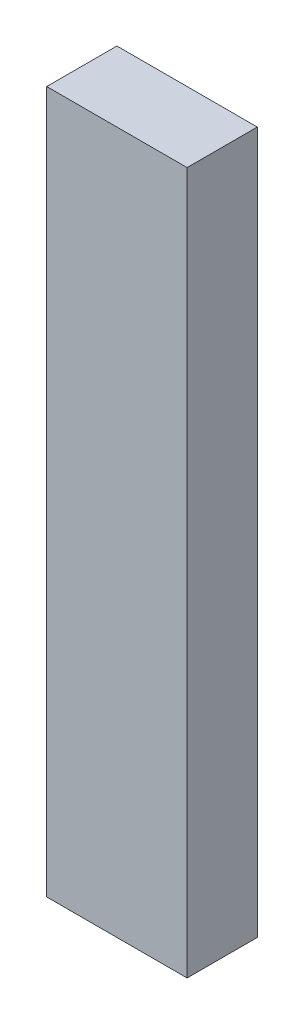
SolidWorks part; units mm, degrees
ref_plane "Front Plane" through (0, 0, 0) normal (0, 0, 1) x (1, 0, 0)
ref_plane "Top Plane" through (0, 0, 0) normal (0, 1, 0) x (1, 0, 0)
ref_plane "Right Plane" through (0, 0, 0) normal (1, 0, 0) x (0, 0, -1)
sketch "Sketch1" plane through (0, 0, 0) normal (0, 1, 0) x (1, 0, 0)
  line L1 (25, -25) -> (-25, -25)
  line L2 (25, -25) -> (25, 25)
  line L3 (25, 25) -> (-25, 25)
  line L4 (-25, -25) -> (-25, 25)
  line L5 (25, -25) -> (-25, 25) construction
  line L6 (25, 25) -> (-25, -25) construction
  point P0 (0, 0)
  dimension "D1" = 50
  dimension "D2" = 50
ref_plane "Plane1" through (0, 1, 0) normal (0, 1, 0) x (1, 0, 0)
sketch "Sketch5" plane through (0, 1, 0) normal (0, 1, 0) x (1, 0, 0)
  line L0 (-25, -25) -> (-25, 25) construction
  line L1 (-4, 2) -> (4, 2)
  line L2 (-4, 2) -> (-4, -2)
  line L3 (-4, -2) -> (4, -2)
  line L4 (4, 2) -> (4, -2)
  line L6 (25, 25) -> (-25, 25) construction
  dimension "D1" = 4
  dimension "D2" = 8
  dimension "D3" = 21
  dimension "D4" = 23
extrude "Boss-Extrude4" add sketch "Sketch5" along normal blind 40 separate body
